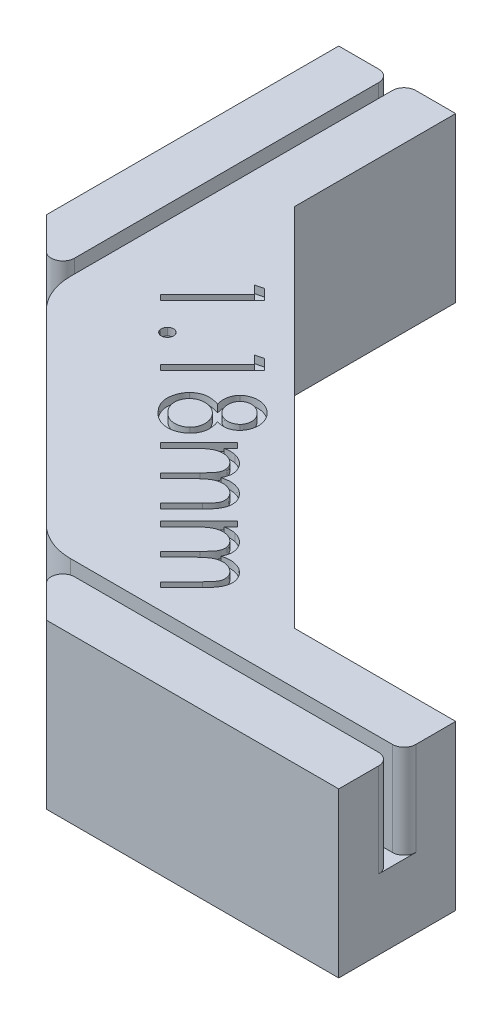
SolidWorks part; units mm, degrees
ref_plane "Front" through (0, 0, 0) normal (0, 0, 1) x (1, 0, 0)
ref_plane "Top" through (0, 0, 0) normal (0, 1, 0) x (1, 0, 0)
ref_plane "Right" through (0, 0, 0) normal (1, 0, 0) x (0, 0, -1)
sketch "Sketch1" plane through (0, 0, 0) normal (0, 1, 0) x (1, 0, 0)
  line L0 (0, 30) -> (0, 55)
  line L1 (0, 55) -> (10, 55)
  line L2 (10, 55) -> (10, 41.2132)
  line L3 (10, 41.2132) -> (41.2132, 10)
  line L4 (41.2132, 10) -> (55, 10)
  line L5 (55, 10) -> (55, 0)
  line L6 (55, 0) -> (30, 0)
  line L7 (30, 0) -> (0, 30)
  line L8 (0, 30) -> (0, 0) construction
  line L9 (0, 0) -> (30, 0) construction
  line L10 (5, 55) -> (5, 25) construction
  line L11 (55, 5) -> (25, 5) construction
  dimension "D1" = 50
  dimension "D2" = 25
  dimension "D3" = 10
  dimension "D4" = 15
extrude "Boss-Extrude1" add sketch "Sketch1" along normal blind 14
sketch "Sketch2" plane through (0, 14, 0) normal (0, 1, 0) x (1, 0, 0)
  line L0 (5, 55) -> (5, 5) construction
  line L1 (10, 55) -> (0, 55) construction
  line L2 (55, 5) -> (5, 5) construction
  line L3 (55, 0) -> (55, 10) construction
  line L4 (5.5875, 55) -> (5.5875, 5.5875)
  line L5 (55, 5.5875) -> (5.5875, 5.5875)
  line L6 (4.4125, 55) -> (4.4125, 4.4125)
  line L7 (55, 4.4125) -> (4.4125, 4.4125)
  line L8 (5.5875, 55) -> (4.4125, 55)
  line L9 (55, 5.5875) -> (55, 4.4125)
  dimension "D1" = 1.175
extrude "Cut-Extrude1" cut sketch "Sketch2" against normal blind 8
sketch "Sketch3" plane through (0, 14, 0) normal (0, 1, 0) x (1, 0, 0)
  line L0 (15, 15) -> (25.6066, 25.6066) construction
  line L1 (5.5875, 24.4125) -> (24.4125, 5.5875) construction
  line L2 (41.2132, 10) -> (10, 41.2132) construction
  line L3 (9.1963, 30.5745) -> (30.5745, 9.1963) construction
  text T0 "1.18mm\r\n"
  point P8 (19.8854, 19.8854)
extrude "Cut-Extrude2" cut sketch "Sketch3" against normal blind 0.64
fillet "Fillet1" radius 1 6 edges at (25.5875, 10, -4.4125) (4.4125, 10, -25.5875) (4.4125, 10, -55) (5.5875, 10, -55) (55, 10, -5.5875) (55, 10, -4.4125)
fillet "Fillet2" radius 5 2 edges at (5.5875, 10, -24.4125) (24.4125, 10, -5.5875)
